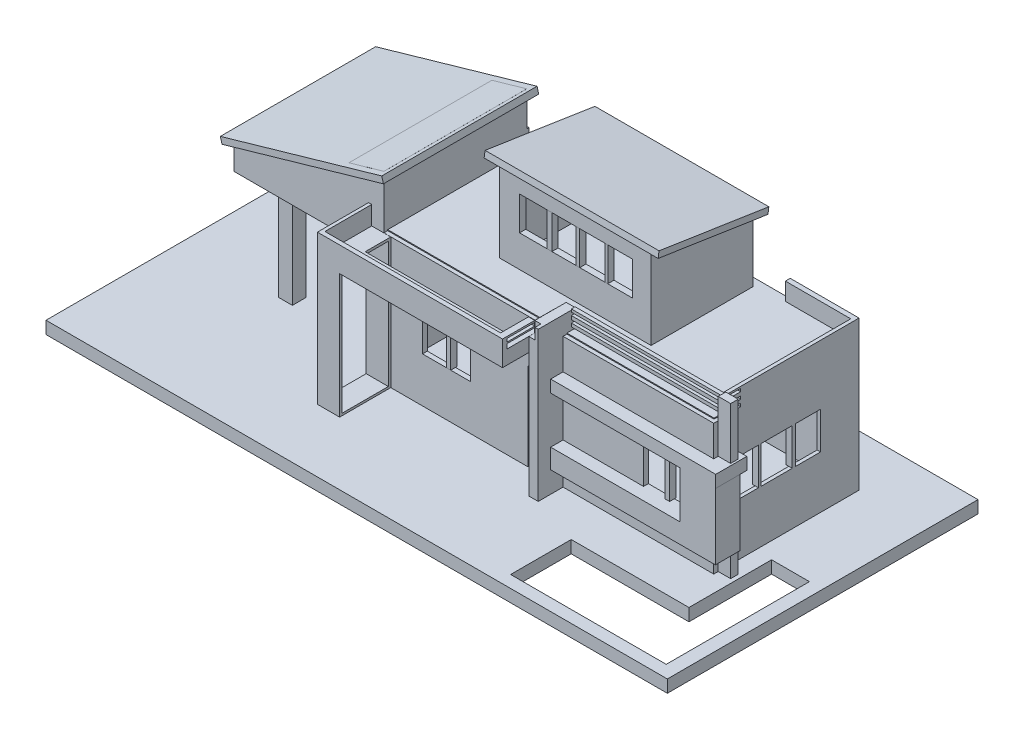
SolidWorks part; units mm, degrees
ref_plane "Front Plane" through (0, 0, 0) normal (0, 0, 1) x (1, 0, 0)
ref_plane "Top Plane" through (0, 0, 0) normal (0, 1, 0) x (1, 0, 0)
ref_plane "Right Plane" through (0, 0, 0) normal (1, 0, 0) x (0, 0, -1)
sketch "Sketch1" plane through (0, 0, 0) normal (0, 1, 0) x (1, 0, 0)
  line L1 (-127, 63.5) -> (127, 63.5)
  line L2 (-127, 63.5) -> (-127, -63.5)
  line L3 (-127, -63.5) -> (127, -63.5)
  line L4 (127, 63.5) -> (127, -63.5)
  line L5 (-127, 63.5) -> (127, -63.5) construction
  line L6 (-127, -63.5) -> (127, 63.5) construction
  point P0 (0, 0)
  dimension "D1" = 254
  dimension "D2" = 127
extrude "Boss-Extrude1" add sketch "Sketch1" along normal blind 5.08
sketch "Sketch2" plane through (0, 5.08, 0) normal (0, 1, 0) x (1, 0, 0)
  line L0 (121.5931, 0) -> (121.5931, -58.5448)
  line L1 (121.5931, -58.5448) -> (57.9819, -58.5448)
  line L2 (57.9819, -58.5448) -> (57.9819, -33.7759)
  line L3 (57.9819, -33.7759) -> (106.1125, -33.7759)
  line L4 (106.1125, -33.7759) -> (106.1125, 0)
  line L5 (106.1125, 0) -> (121.5931, 0)
extrude "Cut-Extrude1" cut sketch "Sketch2" against normal blind 5.08
sketch "Sketch3" plane through (0, 5.08, 0) normal (0, 1, 0) x (1, 0, 0)
  line L1 (97.95, 42.5013) -> (99.3574, 42.5013)
  line L2 (97.95, 42.5013) -> (97.95, -16.8879)
  line L3 (97.95, -16.8879) -> (99.3574, -16.8879)
  line L4 (99.3574, 42.5013) -> (99.3574, -16.8879)
extrude "Boss-Extrude2" add sketch "Sketch3" along normal blind 60.96
sketch "Sketch4" plane through (0, 5.08, 0) normal (0, 1, 0) x (1, 0, 0)
  line L1 (97.95, -16.8879) -> (-41.75, -16.8879)
  line L2 (97.95, -16.8879) -> (97.95, -14.9177)
  line L3 (97.95, -14.9177) -> (-41.75, -14.9177)
  line L4 (-41.75, -16.8879) -> (-41.75, -14.9177)
  line L5 (97.95, 42.5013) -> (-41.75, 42.5013)
  line L6 (97.95, 42.5013) -> (97.95, 40.531)
  line L7 (97.95, 40.531) -> (-41.75, 40.531)
  line L8 (-41.75, 42.5013) -> (-41.75, 40.531)
  dimension "D1" = 139.7
  dimension "D2" = 139.7
extrude "Boss-Extrude3" add sketch "Sketch4" along normal blind 60.96
sketch "Sketch5" plane through (0, 0, 16.8879) normal (0, 0, 1) x (1, 0, 0)
  line L0 (-41.75, 5.08) -> (99.3574, 5.08) construction
  line L1 (70.6479, 40.901) -> (90.6319, 40.901)
  line L2 (70.6479, 40.901) -> (70.6479, 21.7614)
  line L3 (70.6479, 21.7614) -> (90.6319, 21.7614)
  line L4 (90.6319, 40.901) -> (90.6319, 21.7614)
  line L5 (23.3827, 40.901) -> (31.3592, 40.901)
  line L6 (23.3827, 40.901) -> (23.3827, 5.08)
  line L7 (23.3827, 5.08) -> (31.3592, 5.08)
  line L8 (31.3592, 40.901) -> (31.3592, 5.08)
  line L9 (-41.75, 66.04) -> (-41.75, 5.08) construction
  line L10 (-19.6976, 39.0223) -> (0, 39.0223)
  line L11 (-19.6976, 39.0223) -> (-19.6976, 23.5063)
  line L12 (-19.6976, 23.5063) -> (0, 23.5063)
  line L13 (0, 39.0223) -> (0, 23.5063)
  line L14 (99.3574, 66.04) -> (-41.75, 66.04)
  line L15 (99.3574, 66.04) -> (99.3574, 58.4693)
  line L16 (99.3574, 58.4693) -> (-41.75, 58.4693)
  line L17 (-41.75, 66.04) -> (-41.75, 58.4693)
extrude "Cut-Extrude2" cut sketch "Sketch5" against normal blind 5.08
sketch "Sketch6" plane through (99.3574, 0, 0) normal (1, 0, 0) x (0, 0, -1)
  line L1 (-6.7709, 41.6198) -> (26.7689, 41.6198)
  line L2 (-6.7709, 41.6198) -> (-6.7709, 26.4839)
  line L3 (-6.7709, 26.4839) -> (26.7689, 26.4839)
  line L4 (26.7689, 41.6198) -> (26.7689, 26.4839)
extrude "Cut-Extrude3" cut sketch "Sketch6" against normal blind 7.62
sketch "Sketch8" plane through (99.3574, 0, 0) normal (1, 0, 0) x (0, 0, -1)
  line L0 (-16.8879, 5.08) -> (42.5013, 5.08) construction
  line L1 (-15.0584, 67.0773) -> (-11.9623, 67.0773)
  line L2 (-15.0584, 67.0773) -> (-15.0584, 5.08)
  line L3 (-15.0584, 5.08) -> (-11.9623, 5.08)
  line L4 (-11.9623, 67.0773) -> (-11.9623, 5.08)
extrude "Boss-Extrude4" add sketch "Sketch8" along normal blind 5.08
sketch "Sketch11" plane through (0, 0, -40.531) normal (0, 0, 1) x (1, 0, 0)
  line L0 (-41.75, 58.8518) -> (97.95, 58.8518)
  line L1 (-41.75, 66.04) -> (-41.75, 5.08) construction
  line L2 (97.95, 66.04) -> (97.95, 5.08) construction
extrude "Extrude-Thin1" add sketch "Sketch11" along normal blind 55.88 thin
sketch "Sketch13" plane through (0, 0, 16.8879) normal (0, 0, 1) x (1, 0, 0)
  line L0 (31.3592, 5.08) -> (99.3574, 5.08) construction
  line L1 (37.768, 66.04) -> (33.958, 66.04)
  line L2 (37.768, 66.04) -> (37.768, 5.08)
  line L3 (37.768, 5.08) -> (33.958, 5.08)
  line L4 (33.958, 66.04) -> (33.958, 5.08)
  dimension "D1" = 3.81
  dimension "D2" = 60.96
extrude "Boss-Extrude7" add sketch "Sketch13" against normal blind 7.62 and the other way blind 7.62 from offset 2.54
sketch "Sketch14" plane through (0, 0, 16.8879) normal (0, 0, 1) x (1, 0, 0)
  line L0 (37.768, 5.08) -> (37.768, 58.4693) construction
  line L1 (37.768, 45.8738) -> (105.2404, 45.8738)
  line L2 (37.768, 45.8738) -> (37.768, 40.901)
  line L3 (37.768, 40.901) -> (105.2404, 40.901)
  line L4 (105.2404, 45.8738) -> (105.2404, 40.901)
extrude "Boss-Extrude8" add sketch "Sketch14" along normal blind 5.08 and the other way blind 7.62
sketch "Sketch15" plane through (0, 0, 16.8879) normal (0, 0, 1) x (1, 0, 0)
  line L1 (90.6319, 40.901) -> (105.1099, 40.901)
  line L2 (90.6319, 40.901) -> (90.6319, 13.7571)
  line L3 (90.6319, 13.7571) -> (105.1099, 13.7571)
  line L4 (105.1099, 40.901) -> (105.1099, 13.7571)
  dimension "D1" = 14.478
extrude "Boss-Extrude9" add sketch "Sketch15" along normal blind 5.08 and the other way blind 5.08
sketch "Sketch17" plane through (0, 0, 16.8879) normal (0, 0, 1) x (1, 0, 0)
  line L0 (37.768, 5.08) -> (37.768, 40.901) construction
  line L1 (90.6319, 13.7571) -> (37.768, 13.7571)
  line L2 (90.6319, 13.7571) -> (90.6319, 21.7614)
  line L3 (90.6319, 21.7614) -> (37.768, 21.7614)
  line L4 (37.768, 13.7571) -> (37.768, 21.7614)
extrude "Boss-Extrude10" add sketch "Sketch17" along normal blind 5.08
sketch "Sketch19" plane through (0, 58.8518, 0) normal (0, 1, 0) x (1, 0, 0)
  line L0 (37.768, -11.8079) -> (37.768, -15.349) construction
  line L1 (99.3574, -11.9623) -> (37.768, -11.9623)
  line L2 (99.3574, -11.9623) -> (99.3574, -13.5103)
  line L3 (99.3574, -13.5103) -> (37.768, -13.5103)
  line L4 (37.768, -11.9623) -> (37.768, -13.5103)
extrude "Boss-Extrude12" add sketch "Sketch19" along normal blind 7.62
sketch "Sketch20" plane through (0, 0, 13.5103) normal (0, 0, 1) x (1, 0, 0)
  line L0 (37.768, 66.04) -> (37.768, 58.8518) construction
  line L1 (37.768, 65.3348) -> (99.3574, 65.3348)
  line L2 (37.768, 65.3348) -> (37.768, 64.1458)
  line L3 (37.768, 64.1458) -> (99.3574, 64.1458)
  line L4 (99.3574, 65.3348) -> (99.3574, 64.1458)
  line L5 (99.3574, 66.4718) -> (99.3574, 58.8518) construction
  line L7 (37.768, 62.6618) -> (99.3574, 62.6618)
  line L8 (37.768, 62.6618) -> (37.768, 61.4706)
  line L9 (37.768, 61.4706) -> (99.3574, 61.4706)
  line L10 (99.3574, 62.6618) -> (99.3574, 61.4706)
  line L11 (37.768, 60.1117) -> (99.3574, 60.1117)
  line L12 (37.768, 60.1117) -> (37.768, 58.8518)
  line L13 (37.768, 58.8518) -> (99.3574, 58.8518)
  line L14 (99.3574, 60.1117) -> (99.3574, 58.8518)
extrude "Cut-Extrude4" cut sketch "Sketch20" against normal blind 7.62
sketch "Sketch21" plane through (-41.75, 0, 0) normal (-1, 0, 0) x (0, 0, 1)
  line L0 (-63.5, 5.08) -> (63.5, 5.08) construction
  line L1 (-40.531, 56.3118) -> (14.9177, 56.3118)
  line L2 (-40.531, 56.3118) -> (-40.531, 5.08)
  line L3 (-40.531, 5.08) -> (14.9177, 5.08)
  line L4 (14.9177, 56.3118) -> (14.9177, 5.08)
  line L5 (14.9177, 5.08) -> (16.8879, 5.08) construction
extrude "Boss-Extrude13" add sketch "Sketch21" against normal blind 2.54
sketch "Sketch25" plane through (0, 0, 16.8879) normal (0, 0, 1) x (1, 0, 0)
  line L0 (-35.4647, 80.262) -> (-35.4647, 49.5822)
  line L1 (-35.4647, 49.5822) -> (-96.8242, 49.5822)
  line L2 (-96.8242, 49.5822) -> (-96.8242, 62.5296)
  line L3 (-96.8242, 62.5296) -> (-35.4647, 80.262)
extrude "Boss-Extrude15" add sketch "Sketch25" against normal blind 58.42
sketch "Sketch27" plane through (0, 5.08, 0) normal (0, 1, 0) x (1, 0, 0)
  line L1 (-87.5358, -2.2517) -> (-81.9065, -2.2517)
  line L2 (-87.5358, -2.2517) -> (-87.5358, -7.881)
  line L3 (-87.5358, -7.881) -> (-81.9065, -7.881)
  line L4 (-81.9065, -2.2517) -> (-81.9065, -7.881)
  line L5 (-87.5358, 32.0871) -> (-81.9065, 32.0871)
  line L6 (-87.5358, 32.0871) -> (-87.5358, 25.8948)
  line L7 (-87.5358, 25.8948) -> (-81.9065, 25.8948)
  line L8 (-81.9065, 32.0871) -> (-81.9065, 25.8948)
extrude "Boss-Extrude16" add sketch "Sketch27" along normal blind 45.72
sketch "Sketch29" plane through (0, 0, -40.531) normal (0, 0, 1) x (1, 0, 0)
  line L0 (-35.4647, 58.8518) -> (97.95, 58.8518) construction
  line L1 (-35.4647, 66.04) -> (71.2153, 66.04)
  line L2 (-35.4647, 66.04) -> (-35.4647, 58.8518)
  line L3 (-35.4647, 58.8518) -> (71.2153, 58.8518)
  line L4 (71.2153, 66.04) -> (71.2153, 58.8518)
  dimension "D1" = 106.68
extrude "Cut-Extrude5" cut sketch "Sketch29" against normal blind 2.54
sketch "Sketch30" plane through (0, 58.8518, 0) normal (0, 1, 0) x (1, 0, 0)
  line L1 (0, 36.5905) -> (56.8561, 36.5905)
  line L2 (0, 36.5905) -> (0, 0)
  line L3 (0, 0) -> (56.8561, 0)
  line L4 (56.8561, 36.5905) -> (56.8561, 0)
extrude "Extrude-Thin3" add sketch "Sketch30" along normal blind 40.64 thin thin type one direction wall 2.54
sketch "Sketch31" plane through (59.3961, 0, 0) normal (1, 0, 0) x (0, 0, -1)
  line L0 (-2.54, 95.4024) -> (39.1305, 88.9819)
  line L1 (-2.54, 99.4918) -> (-2.54, 58.8518) construction
  line L2 (39.1305, 99.4918) -> (39.1305, 58.8518) construction
  line L3 (39.1305, 88.9819) -> (39.1305, 99.4918)
  line L4 (39.1305, 99.4918) -> (-2.54, 99.4918)
  line L5 (-2.54, 99.4918) -> (-2.54, 95.4024)
extrude "Cut-Extrude6" cut sketch "Sketch31" against normal blind 63.5
sketch "Sketch33" plane through (59.3961, 0, 0) normal (1, 0, 0) x (0, 0, -1)
  line L0 (-4.3627, 95.8318) -> (40.531, 88.9819)
extrude "Extrude-Thin4" add sketch "Sketch33" against normal blind 66.04 and the other way blind 5.08 thin
sketch "Sketch34" plane through (0, 0, 2.54) normal (0, 0, 1) x (1, 0, 0)
  line L1 (5.6293, 85.6323) -> (51.7897, 85.6323)
  line L2 (5.6293, 85.6323) -> (5.6293, 71.8405)
  line L3 (5.6293, 71.8405) -> (51.7897, 71.8405)
  line L4 (51.7897, 85.6323) -> (51.7897, 71.8405)
extrude "Cut-Extrude7" cut sketch "Sketch34" against normal blind 17.78
sketch "Sketch35" plane through (0, 0, 2.54) normal (0, 0, 1) x (1, 0, 0)
  line L0 (51.7897, 85.6323) -> (5.6293, 85.6323) construction
  line L1 (16.8879, 85.6323) -> (18.8582, 85.6323)
  line L2 (16.8879, 85.6323) -> (16.8879, 71.8405)
  line L3 (16.8879, 71.8405) -> (18.8582, 71.8405)
  line L4 (18.8582, 85.6323) -> (18.8582, 71.8405)
  line L5 (5.6293, 71.8405) -> (51.7897, 71.8405) construction
  line L7 (28.7095, 85.6323) -> (30.2359, 85.6323)
  line L8 (28.7095, 85.6323) -> (28.7095, 71.8405)
  line L9 (28.7095, 71.8405) -> (30.2359, 71.8405)
  line L10 (30.2359, 85.6323) -> (30.2359, 71.8405)
  line L11 (40.5093, 85.6323) -> (41.6907, 85.6323)
  line L12 (40.5093, 85.6323) -> (40.5093, 71.8405)
  line L13 (40.5093, 71.8405) -> (41.6907, 71.8405)
  line L14 (41.6907, 85.6323) -> (41.6907, 71.8405)
extrude "Boss-Extrude17" add sketch "Sketch35" against normal blind 2.54 separate body
sketch "Sketch39" plane through (0, 0, 16.8879) normal (0, 0, 1) x (1, 0, 0)
  line L0 (0, 39.0223) -> (-19.6976, 39.0223) construction
  line L1 (-9.8488, 39.0223) -> (-8.1625, 39.0223)
  line L2 (-9.8488, 39.0223) -> (-9.8488, 23.5063)
  line L3 (-9.8488, 23.5063) -> (-8.1625, 23.5063)
  line L4 (-8.1625, 39.0223) -> (-8.1625, 23.5063)
  line L5 (-19.6976, 23.5063) -> (0, 23.5063) construction
extrude "Boss-Extrude18" add sketch "Sketch39" against normal blind 2.54 separate body
sketch "Sketch42" plane through (0, 0, 16.8879) normal (0, 0, 1) x (1, 0, 0)
  line L0 (37.768, 40.901) -> (90.6319, 40.901) construction
  line L1 (79.3733, 40.901) -> (81.3436, 40.901)
  line L2 (79.3733, 40.901) -> (79.3733, 21.7614)
  line L3 (79.3733, 21.7614) -> (81.3436, 21.7614)
  line L4 (81.3436, 40.901) -> (81.3436, 21.7614)
  line L5 (90.6319, 21.7614) -> (37.768, 21.7614) construction
extrude "Boss-Extrude19" add sketch "Sketch42" against normal blind 2.54
sketch "Sketch43" plane through (99.3574, 0, 0) normal (1, 0, 0) x (0, 0, -1)
  line L0 (26.7689, 41.6198) -> (-6.7709, 41.6198) construction
  line L1 (1.4073, 41.6198) -> (2.5332, 41.6198)
  line L2 (1.4073, 41.6198) -> (1.4073, 26.4839)
  line L3 (1.4073, 26.4839) -> (2.5332, 26.4839)
  line L4 (2.5332, 41.6198) -> (2.5332, 26.4839)
  line L5 (-6.7709, 26.4839) -> (26.7689, 26.4839) construction
  line L7 (15.1991, 41.6198) -> (16.4657, 41.6198)
  line L8 (15.1991, 41.6198) -> (15.1991, 26.4839)
  line L9 (15.1991, 26.4839) -> (16.4657, 26.4839)
  line L10 (16.4657, 41.6198) -> (16.4657, 26.4839)
extrude "Boss-Extrude20" add sketch "Sketch43" against normal blind 2.54
sketch "Sketch47" plane through (0, 5.08, 0) normal (0, 1, 0) x (1, 0, 0)
  line L1 (-41.75, -16.8879) -> (-32.6763, -16.8879)
  line L2 (-41.75, -16.8879) -> (-41.75, -37.7924)
  line L3 (-41.75, -37.7924) -> (-32.6763, -37.7924)
  line L4 (-32.6763, -16.8879) -> (-32.6763, -37.7924)
extrude "Boss-Extrude21" add sketch "Sketch47" along normal blind 53.34
sketch "Sketch48" plane through (-32.6763, 0, 0) normal (1, 0, 0) x (0, 0, -1)
  line L1 (-36.8817, 57.3918) -> (-17.8625, 57.3918)
  line L2 (-36.8817, 57.3918) -> (-36.8817, 5.962)
  line L3 (-36.8817, 5.962) -> (-17.8625, 5.962)
  line L4 (-17.8625, 57.3918) -> (-17.8625, 5.962)
extrude "Cut-Extrude9" cut sketch "Sketch48" against normal blind 10.16
sketch "Sketch51" plane through (0, 0, 16.8879) normal (0, 0, 1) x (1, 0, 0)
  line L0 (-99.8189, 61.7235) -> (-33.8315, 80.715)
extrude "Extrude-Thin6" add sketch "Sketch51" against normal blind 60.96 and the other way blind 2.54 thin
sketch "Sketch53" plane through (0, 58.42, 0) normal (0, 1, 0) x (1, 0, 0)
  line L0 (-41.75, -16.8879) -> (-41.75, -37.7924) construction
  line L1 (-41.75, -27.3402) -> (33.918, -27.3402)
  line L2 (-41.75, -27.3402) -> (-41.75, -37.7924)
  line L3 (-41.75, -37.7924) -> (33.918, -37.7924)
  line L4 (33.918, -27.3402) -> (33.918, -37.7924)
extrude "Boss-Extrude22" add sketch "Sketch53" against normal blind 2.54
sketch "Sketch54" plane through (0, 58.42, 0) normal (0, 1, 0) x (1, 0, 0)
  line L1 (33.918, -37.7924) -> (31.3592, -37.7924)
  line L2 (33.918, -37.7924) -> (33.918, -16.8879)
  line L3 (33.918, -16.8879) -> (31.3592, -16.8879)
  line L4 (31.3592, -37.7924) -> (31.3592, -16.8879)
extrude "Boss-Extrude23" add sketch "Sketch54" against normal blind 2.54 and the other way blind 7.62
sketch "Sketch55" plane through (31.3592, 0, 0) normal (-1, 0, 0) x (0, 0, 1)
  line L1 (16.8879, 66.04) -> (36.4311, 66.04)
  line L2 (16.8879, 66.04) -> (16.8879, 61.5835)
  line L3 (16.8879, 61.5835) -> (36.4311, 61.5835)
  line L4 (36.4311, 66.04) -> (36.4311, 61.5835)
extrude "Cut-Extrude10" cut sketch "Sketch55" against normal blind 2.54
sketch "Sketch58" plane through (33.8992, 0, 0) normal (-1, 0, 0) x (0, 0, 1)
  line L0 (36.4311, 66.04) -> (16.8879, 66.04) construction
  line L1 (24.6259, 66.04) -> (36.4311, 66.04)
  line L2 (24.6259, 66.04) -> (24.6259, 61.5835)
  line L3 (24.6259, 61.5835) -> (36.4311, 61.5835)
  line L4 (36.4311, 66.04) -> (36.4311, 61.5835)
  line L5 (16.8879, 61.5835) -> (36.4311, 61.5835) construction
extrude "Cut-Extrude12" cut sketch "Sketch58" against normal blind 2.54
sketch "Sketch61" plane through (0, 58.42, 0) normal (0, 1, 0) x (1, 0, 0)
  line L0 (-41.75, 42.5013) -> (-41.75, -37.7924) construction
  line L1 (33.918, -37.7924) -> (-41.75, -37.7924)
  line L2 (33.918, -37.7924) -> (33.918, -36.029)
  line L3 (33.918, -36.029) -> (-41.75, -36.029)
  line L4 (-41.75, -37.7924) -> (-41.75, -36.029)
extrude "Boss-Extrude25" add sketch "Sketch61" along normal blind 7.62
sketch "Sketch63" plane through (0, 58.42, 0) normal (0, 1, 0) x (1, 0, 0)
  line L0 (31.3592, -36.029) -> (-41.75, -36.029) construction
  line L1 (-41.75, -16.8879) -> (-40.4595, -16.8879)
  line L2 (-41.75, -16.8879) -> (-41.75, -36.029)
  line L3 (-41.75, -36.029) -> (-40.4595, -36.029)
  line L4 (-40.4595, -16.8879) -> (-40.4595, -36.029)
extrude "Boss-Extrude26" add sketch "Sketch63" along normal blind 7.62
sketch "Sketch64" plane through (33.918, 0, 0) normal (1, 0, 0) x (0, 0, -1)
  line L0 (-36.029, 66.04) -> (-36.029, 61.5835) construction
  line L1 (-36.029, 63.4671) -> (-24.6259, 63.4671)
  line L2 (-36.029, 63.4671) -> (-36.029, 64.0374)
  line L3 (-36.029, 64.0374) -> (-24.6259, 64.0374)
  line L4 (-24.6259, 63.4671) -> (-24.6259, 64.0374)
  line L5 (-24.6259, 61.5835) -> (-24.6259, 66.04) construction
  line L6 (-37.7924, 66.04) -> (-36.029, 66.04) construction
  line L7 (-36.029, 66.04) -> (-24.6259, 66.04)
  line L8 (-36.029, 66.04) -> (-36.029, 65.3325)
  line L9 (-36.029, 65.3325) -> (-24.6259, 65.3325)
  line L10 (-24.6259, 66.04) -> (-24.6259, 65.3325)
extrude "Boss-Extrude27" add sketch "Sketch64" against normal blind 2.54
